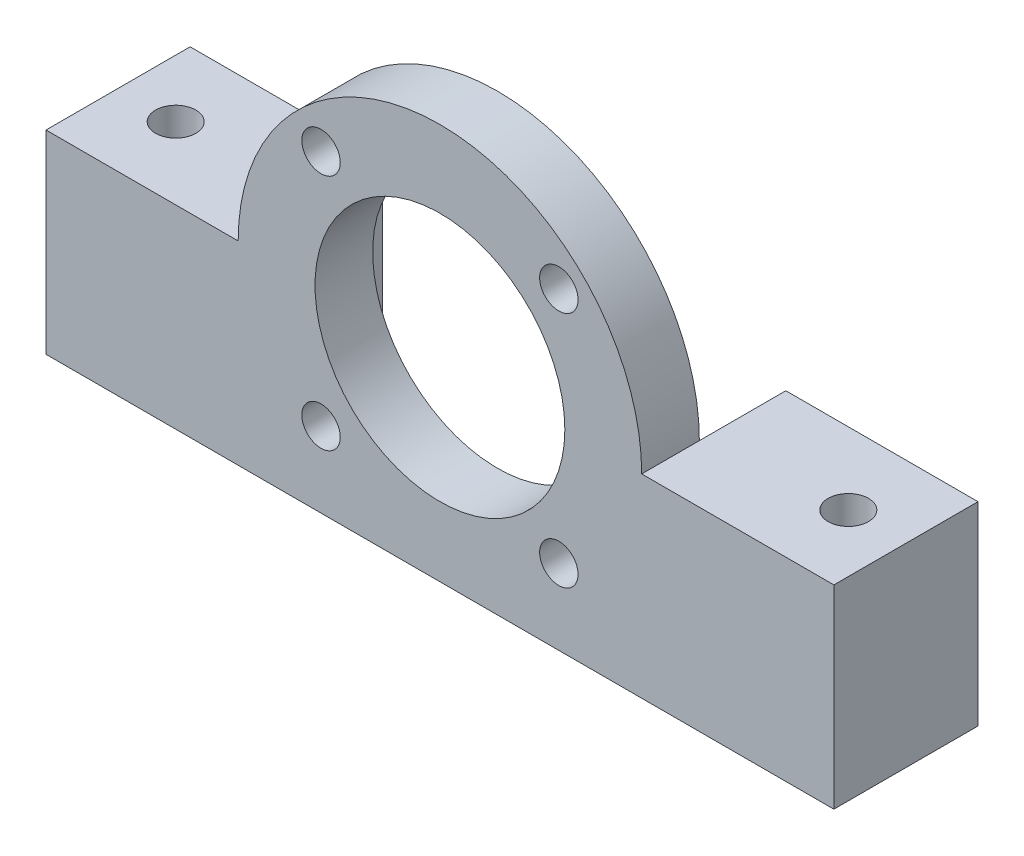
SolidWorks part; units mm, degrees
material "6061 合金"
ref_plane "前视基准面" through (0, 0, 0) normal (0, 0, 1) x (1, 0, 0)
ref_plane "上视基准面" through (0, 0, 0) normal (0, 1, 0) x (1, 0, 0)
ref_plane "右视基准面" through (0, 0, 0) normal (1, 0, 0) x (0, 0, -1)
sketch "草图1" plane through (0, 0, 0) normal (0, 0, 1) x (1, 0, 0)
  line L0 (0, 0) -> (0, 76.2204) construction
  line L1 (-21, 20.22) -> (-21, 0)
  line L2 (-21, 0) -> (21, 0)
  line L3 (21, 0) -> (21, 20.22)
  line L4 (-12.3744, 32.5944) -> (12.3744, 7.8456) construction
  line L5 (12.3744, 32.5944) -> (-12.3744, 7.8456) construction
  arc A0 (21, 20.22) -> (-21, 20.22) centre (0, 20.22) ccw
  circle A1 centre (0, 20.22) radius 13
  circle A2 centre (0, 20.22) radius 17.5 construction
  circle A3 centre (-12.3744, 32.5944) radius 2
  circle A4 centre (12.3744, 32.5944) radius 2
  circle A5 centre (12.3744, 7.8456) radius 2
  circle A6 centre (-12.3744, 7.8456) radius 2
  dimension "D1" = 42
  dimension "D3" = 26
  dimension "D4" = 35
  dimension "D5" = 4
  dimension "D2" = 20.22
extrude "凸台-拉伸1" add sketch "草图1" along normal blind 6
sketch "草图2" plane through (0, 0, 6) normal (0, 0, 1) x (1, 0, 0)
  line L0 (0, 0) -> (0, -50000) construction
  line L1 (-41, 20.22) -> (-21, 20.22)
  line L2 (-41, 20.22) -> (-41, 0)
  line L3 (-41, 0) -> (-21, 0)
  line L4 (-21, 20.22) -> (-21, 0)
  line L5 (-41, 20.22) -> (-21, 0) construction
  line L6 (-41, 0) -> (-21, 20.22) construction
  line L7 (41, 0) -> (21, 0)
  line L8 (21, 20.22) -> (21, 0)
  line L9 (41, 20.22) -> (21, 20.22)
  line L10 (41, 20.22) -> (41, 0)
  point P0 (-31, 10.11)
  dimension "D1" = 20
extrude "凸台-拉伸2" add sketch "草图2" against normal blind 15
sketch "草图3" plane through (0, 20.22, 0) normal (0, 1, 0) x (1, 0, 0)
  line L0 (-41, 1.5) -> (49959, 1.5) construction
  line L2 (-21, -6) -> (-41, -6) construction
  line L3 (0, 0) -> (0, -50000) construction
  line L4 (-41, 9) -> (-41, -6) construction
  circle A0 centre (-35, 1.5) radius 2.1
  circle A1 centre (35, 1.5) radius 2.1
  dimension "D2" = 6
  dimension "D3" = 4.2
  dimension "D1" = 7.5
extrude "切除-拉伸1" cut sketch "草图3" against normal through all
